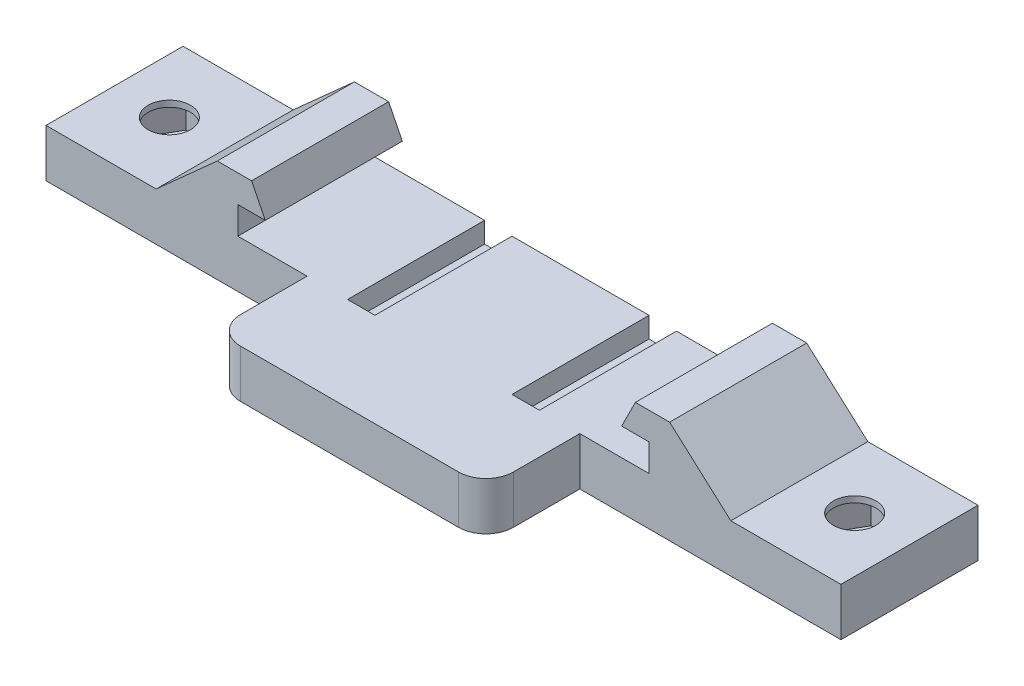
SolidWorks part; units mm, degrees
ref_plane "Front Plane" through (0, 0, 0) normal (0, 0, 1) x (1, 0, 0)
ref_plane "Top Plane" through (0, 0, 0) normal (0, 1, 0) x (1, 0, 0)
ref_plane "Right Plane" through (0, 0, 0) normal (1, 0, 0) x (0, 0, -1)
sketch "Sketch1" plane through (0, 0, 0) normal (0, 1, 0) x (1, 0, 0)
  line L0 (-44.2539, 0) -> (44.2539, 0) construction
  line L1 (-29, 5) -> (29, 5)
  line L2 (-29, 5) -> (-29, -5)
  line L3 (-29, -5) -> (29, -5)
  line L4 (29, 5) -> (29, -5)
  line L5 (0, -44.7868) -> (0, 44.7868) construction
  dimension "D1" = 10
  dimension "D2" = 5
  dimension "D3" = 58
  dimension "D4" = 29
extrude "Boss-Extrude1" add sketch "Sketch1" along normal mid plane 3.5
sketch "Sketch2" plane through (0, 1.75, 0) normal (0, 1, 0) x (1, 0, 0)
  line L0 (-44.2539, 0) -> (44.2539, 0) construction
  line L1 (0, -44.7868) -> (0, 44.7868) construction
  circle A0 centre (-25, 0) radius 1.55
  circle A1 centre (25, 0) radius 1.55
  dimension "D1" = 3.1
  dimension "D2" = 50
  dimension "D3" = 25
extrude "Cut-Extrude1" cut sketch "Sketch2" against normal up to surface (3.5 mm away) up to face at (0, -1.75, 0)
sketch "Sketch4" plane through (0, 0, 0) normal (0, 1, 0) x (1, 0, 0)
  line L0 (-28.2909, 0) -> (-28.2909, -2.85)
  line L1 (-21.7091, 0) -> (-23.3546, 2.85)
  line L2 (-23.3546, 2.85) -> (-26.6454, 2.85)
  line L3 (-26.6454, 2.85) -> (-28.2909, 0)
  line L5 (-26.6454, -2.85) -> (-23.3546, -2.85)
  line L7 (28.2909, 0) -> (26.6454, 2.85)
  line L8 (26.6454, 2.85) -> (23.3546, 2.85)
  line L9 (23.3546, 2.85) -> (21.7091, 0)
  line L11 (23.3546, -2.85) -> (26.6454, -2.85)
  line L13 (-44.2539, 0) -> (44.2539, 0) construction
  line L14 (-23.3546, -2.85) -> (-21.7091, 0) [skipped]
  line L15 (-28.2909, 0) -> (-26.6454, -2.85) [skipped]
  line L16 (21.7091, 0) -> (23.3546, -2.85) [skipped]
  line L17 (26.6454, -2.85) -> (28.2909, 0) [skipped]
  line L18 (-28.2909, -2.85) -> (-26.6454, -2.85)
  line L19 (-21.7091, 0) -> (-21.7091, -2.85)
  line L20 (-21.7091, -2.85) -> (-23.3546, -2.85)
  line L21 (21.7091, 0) -> (21.7091, -2.85)
  line L22 (21.7091, -2.85) -> (23.3546, -2.85)
  line L23 (26.6454, -2.85) -> (28.2909, -2.85)
  line L24 (28.2909, -2.85) -> (28.2909, 0)
  circle A0 centre (-25, 0) radius 2.85 construction
  circle A1 centre (25, 0) radius 2.85 construction
  dimension "D1" = 5.7
extrude "Cut-Extrude2" cut sketch "Sketch4" against normal mid plane 2.6
sketch "Sketch5" plane through (0, 0, 0) normal (0, 1, 0) x (1, 0, 0)
  line L0 (-44.2539, 0) -> (44.2539, 0) construction
  line L1 (-9.95, 11.85) -> (9.95, 11.85)
  line L2 (-9.95, 11.85) -> (-9.95, -11.85)
  line L3 (-9.95, -11.85) -> (9.95, -11.85)
  line L4 (9.95, 11.85) -> (9.95, -11.85)
  line L5 (0, -44.7868) -> (0, 44.7868) construction
  dimension "D1" = 19.9
  dimension "D2" = 23.7
  dimension "D3" = 11.85
  dimension "D4" = 9.95
extrude "Boss-Extrude2" add sketch "Sketch5" along normal mid plane 3.5
fillet "Fillet1" radius 2 2 edges at (9.95, 0, 11.85) (-9.95, 0, 11.85)
sketch "Sketch6" plane through (0, 0, 0) normal (0, 0, 1) x (1, 0, 0)
  line L0 (-20.9645, 1.75) -> (-16.5, 5.75)
  line L1 (-29, 1.75) -> (-9.95, 1.75) construction
  line L2 (-16.5, 5.75) -> (-14, 5.75)
  line L3 (-14, 5.75) -> (-13, 3.75)
  line L4 (-13, 3.75) -> (-15, 3.75)
  line L5 (-15, 3.75) -> (-15, 1.75)
  line L6 (-20.9645, 1.75) -> (-15, 1.75)
  line L8 (0, -44.7868) -> (0, 44.7868) construction
  point P4 (-8.1362, 5.0376)
  point P9 (-10.3547, 1.75)
  point P10 (-10.4741, 4.9181)
  point P11 (-12.5225, 1.75)
  dimension "D1" = 2
  dimension "D2" = 2
  dimension "D4" = 4
  dimension "D6" = 1
  dimension "D7" = 15
extrude "Boss-Extrude3" add sketch "Sketch6" along normal mid plane 10
mirror "Mirror1" about plane through (0, 0, 0) normal (1, 0, 0) of "Boss-Extrude3"
sketch "Sketch7" plane through (0, 1.75, 0) normal (0, 1, 0) x (1, 0, 0)
  line L0 (15, 5) -> (9.95, 5) construction
  line L1 (-7, 5) -> (-5, 5)
  line L2 (-7, 5) -> (-7, -5)
  line L3 (-7, -5) -> (-5, -5)
  line L4 (-5, 5) -> (-5, -5)
  line L5 (-15, -5) -> (-9.95, -5) construction
  line L6 (0, -44.7868) -> (0, 44.7868) construction
  line L7 (5, 5) -> (7, 5)
  line L8 (5, 5) -> (5, -5)
  line L9 (5, -5) -> (7, -5)
  line L10 (7, 5) -> (7, -5)
  dimension "D1" = 2
  dimension "D2" = 14
  dimension "D3" = 7
extrude "Cut-Extrude3" cut sketch "Sketch7" against normal blind 1.5
sketch "Sketch8" plane through (0, 0, 0) normal (0, 1, 0) x (1, 0, 0)
  line L0 (-9.95, 5) -> (-15, 5) construction
  line L1 (-11.471, 5) -> (12.3379, 5)
  line L2 (-11.471, 5) -> (-11.471, 19.9347)
  line L3 (-11.471, 19.9347) -> (12.3379, 19.9347)
  line L4 (12.3379, 5) -> (12.3379, 19.9347)
extrude "Cut-Extrude4" cut sketch "Sketch8" against normal mid plane 10
equation "\"len\"=58"
equation "\"D3@Sketch1\"=\"len\""
equation "\"D4@Sketch1\"=\"len\"/2"
equation "\"bwid\"=19.9"
equation "\"D1@Sketch5\"=\"bwid\""
equation "\"blen\"=23.7"
equation "\"D2@Sketch5\"=\"blen\""
equation "\"D3@Sketch5\"=\"blen\"/2"
equation "\"D4@Sketch5\"=\"bwid\"/2"
